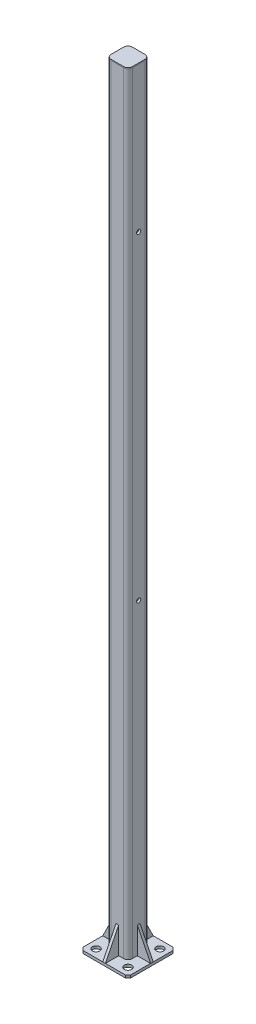
SolidWorks part; units mm, degrees
material "普通碳钢"
ref_plane "前视基准面" through (0, 0, 0) normal (0, 0, 1) x (1, 0, 0)
ref_plane "上视基准面" through (0, 0, 0) normal (0, 1, 0) x (1, 0, 0)
ref_plane "右视基准面" through (0, 0, 0) normal (1, 0, 0) x (0, 0, -1)
sketch "草图1" plane through (0, 0, 0) normal (0, 0, 1) x (1, 0, 0)
  line L0 (0, 0) -> (0, 1450)
  dimension "D1" = 1450
other "结构构件1"
ref_plane "基准面1" through (0, 0, 0) normal (0, 1, 0) x (-1, 0, 0)
sketch "Sketch1" plane through (0, 0, 0) normal (0, 1, 0) x (-1, 0, 0)
  line L0 (-12, -16) -> (12, -16)
  line L1 (-16, -12) -> (-16, 12)
  line L2 (12, 16) -> (-12, 16)
  line L3 (16, 12) -> (16, -12)
  line L4 (-12, -20) -> (12, -20)
  line L5 (-20, -12) -> (-20, 12)
  line L6 (12, 20) -> (-12, 20)
  line L7 (20, 12) -> (20, -12)
  arc A0 (20, 12) -> (12, 20) centre (12, 12) ccw
  arc A1 (12, -20) -> (20, -12) centre (12, -12) ccw
  arc A2 (-20, -12) -> (-12, -20) centre (-12, -12) ccw
  arc A3 (-12, 20) -> (-20, 12) centre (-12, 12) ccw
  arc A4 (-12, 16) -> (-16, 12) centre (-12, 12) ccw
  arc A5 (16, 12) -> (12, 16) centre (12, 12) ccw
  arc A6 (12, -16) -> (16, -12) centre (12, -12) ccw
  arc A7 (-16, -12) -> (-12, -16) centre (-12, -12) ccw
  point P0 (-20, 0)
  point P1 (20, 0)
  point P2 (0, 20)
  point P3 (0, -20)
  point P4 (0, 0)
  point P5 (-20, -20)
  point P6 (20, -20)
  point P7 (20, 20)
  point P8 (-20, 20)
  point P33 (0, 0)
  dimension "D1" = 8
  dimension "Thickness" = 4
  dimension "V_leg" = 40
sketch "草图3" plane through (0, 0, 0) normal (0, -1, 0) x (1, 0, 0)
  line L0 (0, 38.0086) -> (0, 0) construction
  line L1 (0, 0) -> (51.2514, 0) construction
  line L3 (-45, 45) -> (45, 45)
  line L4 (-45, 45) -> (-45, -45)
  line L5 (-45, -45) -> (45, -45)
  line L6 (45, 45) -> (45, -45)
  circle A0 centre (30, 30) radius 7
  circle A1 centre (30, -30) radius 7
  circle A2 centre (-30, 30) radius 7
  circle A3 centre (-30, -30) radius 7
  dimension "D3" = 14
  dimension "D4" = 60
  dimension "D5" = 60
  dimension "D1" = 90
  dimension "D2" = 90
extrude "凸台-拉伸1" add sketch "草图3" along normal blind 5 separate body
chamfer "倒角1" distance 5 angle 45 4 edges at (-45, -2.5, -45) (-45, -2.5, 45) (45, -2.5, 45) (45, -2.5, -45)
sketch "草图4" plane through (0, 1450, 0) normal (0, 1, 0) x (1, 0, 0)
  line L4 (-12, -20) -> (12, -20)
  line L5 (20, -12) -> (20, 12)
  line L6 (12, 20) -> (-12, 20)
  line L7 (-20, 12) -> (-20, -12)
  line L8 (-12, -20) -> (12, -20)
  line L9 (20, -12) -> (20, 12)
  line L10 (12, 20) -> (-12, 20)
  line L11 (-20, 12) -> (-20, -12)
  arc A4 (-20, -12) -> (-12, -20) centre (-12, -12) ccw
  arc A5 (12, -20) -> (20, -12) centre (12, -12) ccw
  arc A6 (20, 12) -> (12, 20) centre (12, 12) ccw
  arc A7 (-12, 20) -> (-20, 12) centre (-12, 12) ccw
  arc A8 (-20, -12) -> (-12, -20) centre (-12, -12) ccw
  arc A9 (12, -20) -> (20, -12) centre (12, -12) ccw
  arc A10 (20, 12) -> (12, 20) centre (12, 12) ccw
  arc A11 (-12, 20) -> (-20, 12) centre (-12, 12) ccw
  dimension "D1" = 0
extrude "凸台-拉伸2" add sketch "草图4" along normal blind 2 separate body
sketch "草图5" plane through (-20, 0, 0) normal (-1, 0, 0) x (0, 0, 1)
  line L0 (0, 1450) -> (0, 0) construction
  line L1 (-12, 1450) -> (12, 1450) construction
  line L2 (0, 577) -> (162.9027, 577) construction
  circle A0 centre (0, 577) radius 4
  circle A1 centre (0, 1177) radius 4
  circle A2 centre (0, -23) radius 4
  circle A3 centre (0, -23) radius 4
  dimension "D2" = 8
  dimension "D3" = 8
  dimension "D4" = 1200
  dimension "D1" = 873
extrude "切除-拉伸1" cut sketch "草图5" against normal through all contours A2 | A0 | A1
sketch "草图6" plane through (0, 0, 0) normal (0, 0, 1) x (1, 0, 0)
  line L0 (20, 0) -> (20, 50)
  line L1 (20, 1450) -> (20, 0) construction
  line L2 (20, 50) -> (45, 0)
  line L3 (40, 0) -> (45, 0) construction
  line L4 (45, 0) -> (20, 0)
  line L5 (0, 0) -> (0, 79.0081) construction
  line L6 (-45, 0) -> (-20, 0)
  line L7 (-20, 50) -> (-45, 0)
  line L8 (-20, 0) -> (-20, 50)
  dimension "D1" = 50
  dimension "D2" = 25
extrude "凸台-拉伸3" add sketch "草图6" along normal mid plane 5 separate body
sketch "草图7" plane through (0, 0, 0) normal (1, 0, 0) x (0, 0, -1)
  line L0 (20, 50) -> (20, 0)
  line L1 (20, 1450) -> (20, 0) construction
  line L2 (20, 0) -> (45, 0)
  line L3 (45, 0) -> (20, 50)
  line L4 (0, 89.4436) -> (0, 0) construction
  line L5 (-45, 0) -> (-20, 50)
  line L6 (-20, 0) -> (-45, 0)
  line L7 (-20, 50) -> (-20, 0)
  dimension "D1" = 50
extrude "凸台-拉伸4" add sketch "草图7" along normal mid plane 5 separate body
